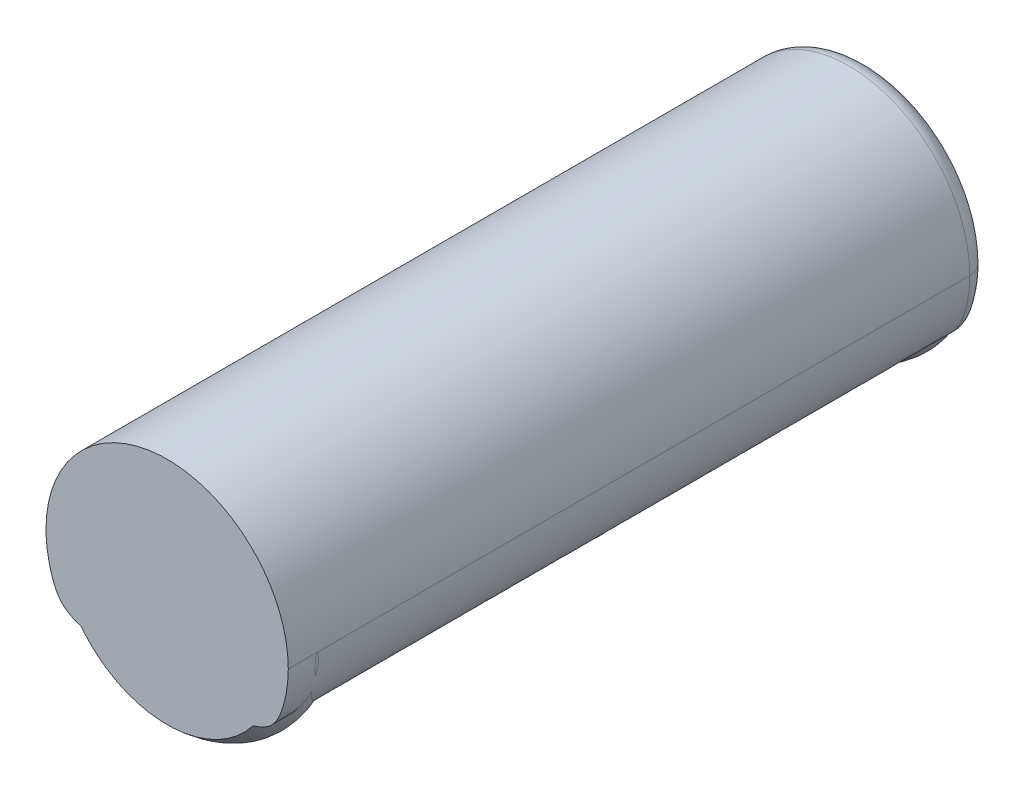
SolidWorks part; units mm, degrees
ref_plane "Front Plane" through (0, 0, 0) normal (0, 0, 1) x (1, 0, 0)
ref_plane "Top Plane" through (0, 0, 0) normal (0, 1, 0) x (1, 0, 0)
ref_plane "Right Plane" through (0, 0, 0) normal (1, 0, 0) x (0, 0, -1)
sketch "Sketch1" plane through (0, 0, 0) normal (1, 0, 0) x (0, 0, -1)
  line L0 (0, 0) -> (88.9, 0) construction
  line L1 (88.9, 0) -> (88.9, -13.97) construction
  line L2 (91.6766, -10.7435) -> (-1.1011, -10.7435) construction
  line L3 (-1.1011, -13.97) -> (-1.1011, 0)
  line L4 (88.9, -13.97) -> (88.9, 0)
  line L5 (-1.1011, 0) -> (88.9, 0)
  line L6 (88.9, 0) -> (-1.1011, 0)
  spline S0 degree 3 poles (88.9, -13.97) (83.8223, -17.6205) (77.2113, -6.8374) (68.7605, -14.7499) (61.0109, -14.8488) (54.6423, -8.5316) (48.0591, -14.7944) (40.3498, -14.9657) (34.2227, -8.5135) (27.7784, -14.8221) (20.0256, -14.8077) (11.419, -6.4554) (4.488, -18.9376) (-1.1011, -13.97) knots 0 0 0 0 0.148512 0.232303 0.300118 0.378852 0.462643 0.532682 0.606431 0.690222 0.758038 0.837778 1 1 1 1
revolve "Revolve1" add sketch "Sketch1" angle 180 mid plane about L0
sketch "Sketch2" plane through (0, 0, -88.9) normal (0, 0, -1) x (-1, 0, 0)
  line L1 (0, 0) -> (15.5474, 0) construction
  line L2 (-13.97, 0) -> (13.97, 0) construction
  line L3 (-15.5474, 0) -> (15.5474, 0)
  arc A0 (-15.5474, 0) -> (15.5474, 0) centre (0, 0) ccw construction
  arc A1 (15.5474, 0) -> (-15.5474, 0) centre (0, 0) ccw
extrude "Boss-Extrude1" add sketch "Sketch2" against normal up to vertex (90.0011 mm away)
sketch "Sketch4" plane through (0, 0, -88.9) normal (0, 0, -1) x (-1, 0, 0)
  line L0 (0, 0) -> (0, -4.6964) construction
  line L1 (1.0903, -8.8522) -> (-1.0903, -8.8522) construction
  line L2 (-15.5474, 0) -> (15.5474, 0)
  arc A0 (-15.5474, 0) -> (15.5474, 0) centre (0, 0) ccw construction
  arc A1 (-15.5474, 0) -> (15.5474, 0) centre (0, 0) ccw construction
  arc A2 (-13.97, 0) -> (13.97, 0) centre (0, 0) ccw construction
  spline S0 degree 3 poles (-15.5474, 0) (-15.5329, -1.6232) (-15.1797, -4.0864) (-13.7459, -7.4548) (-9.7121, -9.3425) (-5.0419, -8.7031) (-1.3628, -8.8522) (0, -8.8522) knots 0 0 0 0 0.222162 0.35674 0.485157 0.808536 1 1 1 1
  spline S1 degree 3 poles (15.5474, 0) (15.5329, -1.6232) (15.1797, -4.0864) (13.7459, -7.4548) (9.7121, -9.3425) (5.0419, -8.7031) (1.3628, -8.8522) (0, -8.8522) knots 0 0 0 0 0.222162 0.35674 0.485157 0.808536 1 1 1 1
extrude "Boss-Extrude3" add sketch "Sketch4" against normal up to vertex (90.0011 mm away)
fillet "Fillet1" radius 2.54 4 edges at (0, -13.97, -88.9) (0, 15.5474, -88.9)
